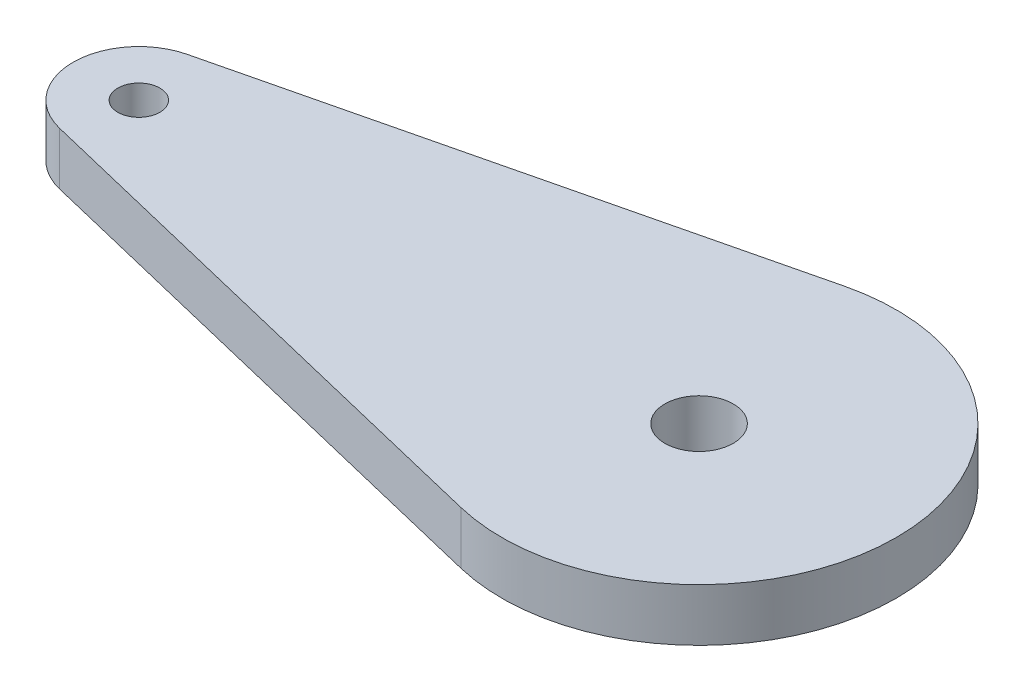
SolidWorks part; units mm, degrees
ref_plane "正面" through (0, 0, 0) normal (0, 0, 1) x (1, 0, 0)
ref_plane "平面" through (0, 0, 0) normal (0, 1, 0) x (1, 0, 0)
ref_plane "右側面" through (0, 0, 0) normal (1, 0, 0) x (0, 0, -1)
sketch "ｽｹｯﾁ1" plane through (0, 0, 0) normal (0, 1, 0) x (1, 0, 0)
  line L0 (0, 0) -> (110, 0) construction
  line L1 (-1.1737, -4.8603) -> (39.0789, -14.5809)
  line L3 (-1.1737, 4.8603) -> (39.0789, 14.5809)
  circle A0 centre (0, 0) radius 1.6
  circle A1 centre (42.6, 0) radius 2.6
  arc A2 (-1.1737, 4.8603) -> (-1.1737, -4.8603) centre (0, 0) ccw
  arc A3 (39.0789, -14.5809) -> (39.0789, 14.5809) centre (42.6, 0) ccw
  dimension "D5" = 3.2
  dimension "D1" = 5
  dimension "D2" = 15
  dimension "D3" = 5.2
  dimension "D4" = 42.6
extrude "ﾎﾞｽ - 押し出し1" add sketch "ｽｹｯﾁ1" along normal blind 4
